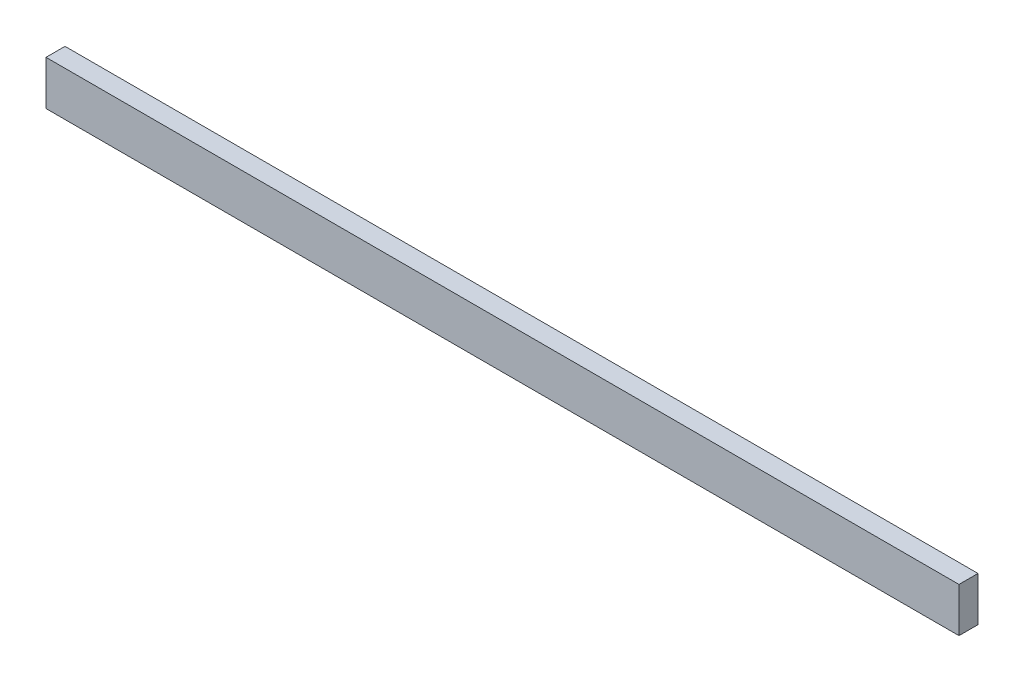
SolidWorks part; units mm, degrees
material "Pine"
ref_plane "Front Plane" through (0, 0, 0) normal (0, 0, 1) x (1, 0, 0)
ref_plane "Top Plane" through (0, 0, 0) normal (0, 1, 0) x (1, 0, 0)
ref_plane "Right Plane" through (0, 0, 0) normal (1, 0, 0) x (0, 0, -1)
sketch "Sketch1" plane through (0, 0, 0) normal (1, 0, 0) x (0, 0, -1)
  line L1 (0, 0) -> (38.1, 0)
  line L2 (0, 0) -> (0, 88.9)
  line L3 (0, 88.9) -> (38.1, 88.9)
  line L4 (38.1, 0) -> (38.1, 88.9)
  dimension "D1" = 38.1
  dimension "D2" = 88.9
extrude "Boss-Extrude1" add sketch "Sketch1" along normal blind 1828.8
